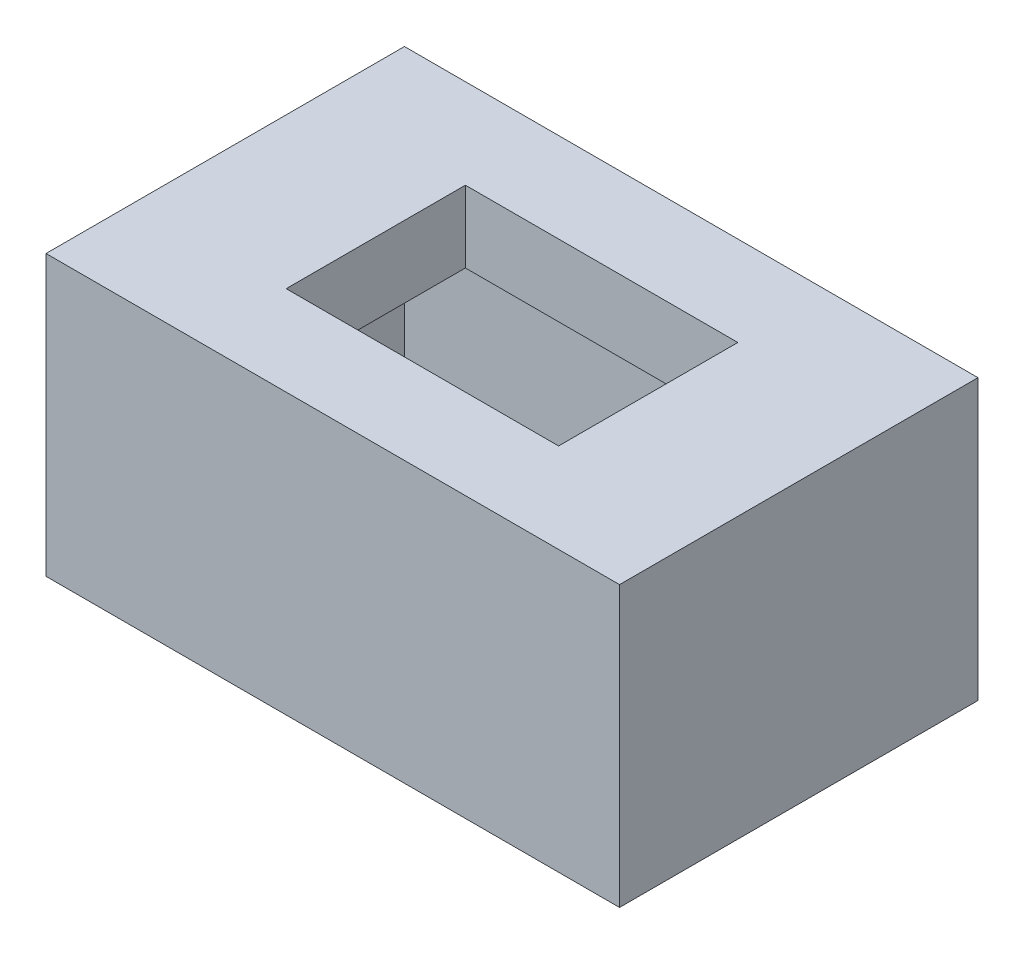
SolidWorks part; units mm, degrees
ref_plane "정면" through (0, 0, 0) normal (0, 0, 1) x (1, 0, 0)
ref_plane "윗면" through (0, 0, 0) normal (0, 1, 0) x (1, 0, 0)
ref_plane "우측면" through (0, 0, 0) normal (1, 0, 0) x (0, 0, -1)
sketch "스케치1" plane through (0, 0, 0) normal (0, 1, 0) x (1, 0, 0)
  line L1 (-40, 25) -> (40, 25)
  line L2 (-40, 25) -> (-40, -25)
  line L3 (-40, -25) -> (40, -25)
  line L4 (40, 25) -> (40, -25)
  line L5 (-40, 25) -> (40, -25) construction
  line L6 (-40, -25) -> (40, 25) construction
  point P0 (0, 0)
  dimension "D1" = 80
  dimension "D2" = 50
extrude "보스-돌출1" add sketch "스케치1" along normal blind 40
sketch "스케치2" plane through (0, 0, 0) normal (0, -1, 0) x (1, 0, 0)
  line L0 (35, -20) -> (35, 20)
  line L1 (35, 20) -> (-35, 20)
  line L2 (-35, 20) -> (-35, -20)
  line L3 (-35, -20) -> (35, -20)
  line L12 (-40, 25) -> (40, 25) construction
  line L13 (-40, -25) -> (-40, 25) construction
  line L14 (40, 25) -> (40, -25) construction
  line L15 (40, -25) -> (-40, -25) construction
  dimension "D1" = 5
  dimension "D2" = 5
  dimension "D3" = 5
  dimension "D4" = 5
extrude "컷-돌출1" cut sketch "스케치2" against normal blind 30
sketch "스케치4" plane through (0, 40, 0) normal (0, 1, 0) x (1, 0, 0)
  line L1 (-19, -12.5) -> (19, -12.5)
  line L2 (-19, -12.5) -> (-19, 12.5)
  line L3 (-19, 12.5) -> (19, 12.5)
  line L4 (19, -12.5) -> (19, 12.5)
  line L5 (-19, -12.5) -> (19, 12.5) construction
  line L6 (-19, 12.5) -> (19, -12.5) construction
  point P0 (0, 0)
  dimension "D1" = 38
  dimension "D2" = 25
extrude "컷-돌출2" cut sketch "스케치4" against normal blind 30
sketch "스케치7" plane through (0, 0, 0) normal (0, -1, 0) x (1, 0, 0)
  line L0 (37.5, -22.5) -> (37.5, 22.5)
  line L1 (37.5, 22.5) -> (-37.5, 22.5)
  line L2 (-37.5, 22.5) -> (-37.5, -22.5)
  line L3 (-37.5, -22.5) -> (37.5, -22.5)
  line L4 (40, -25) -> (40, 25)
  line L5 (40, 25) -> (-40, 25)
  line L6 (-40, 25) -> (-40, -25)
  line L7 (-40, -25) -> (40, -25)
  line L8 (40, -25) -> (40, 25)
  line L9 (40, 25) -> (-40, 25)
  line L10 (-40, 25) -> (-40, -25)
  line L11 (-40, -25) -> (40, -25)
  dimension "D1" = 0
  dimension "D2" = 2.5
extrude "컷-돌출3" cut sketch "스케치7" against normal blind 1
sketch "스케치8" plane through (0, 1, 0) normal (0, -1, 0) x (1, 0, 0)
  line L0 (-37.5, -22.5) -> (37.5, -22.5) construction
  line L1 (37.5, -22.5) -> (37.5, 22.5) construction
  line L2 (37.5, 22.5) -> (-37.5, 22.5) construction
  line L3 (-37.5, 22.5) -> (-37.5, -22.5) construction
  line L4 (-40, -25) -> (40, -25) construction
  line L5 (40, -25) -> (40, 25) construction
  line L6 (40, 25) -> (-40, 25) construction
  line L7 (-40, 25) -> (-40, -25) construction
  line L8 (-37.5, -22.5) -> (37.5, -22.5)
  line L9 (37.5, -22.5) -> (37.5, 22.5)
  line L10 (37.5, 22.5) -> (-37.5, 22.5)
  line L11 (-37.5, 22.5) -> (-37.5, -22.5)
  line L12 (-40, -25) -> (40, -25)
  line L13 (40, -25) -> (40, 25)
  line L14 (40, 25) -> (-40, 25)
  line L15 (-40, 25) -> (-40, -25)
  line L16 (-35, -20) -> (35, -20) construction
  line L17 (35, -20) -> (35, 20) construction
  line L18 (35, 20) -> (-35, 20) construction
  line L19 (-35, 20) -> (-35, -20) construction
  line L20 (-37.5, -22.5) -> (37.5, -22.5)
  line L21 (37.5, -22.5) -> (37.5, 22.5)
  line L22 (37.5, 22.5) -> (-37.5, 22.5)
  line L23 (-37.5, 22.5) -> (-37.5, -22.5)
  line L24 (-37.5, -22.5) -> (37.5, -22.5)
  line L25 (37.5, -22.5) -> (37.5, 22.5)
  line L26 (37.5, 22.5) -> (-37.5, 22.5)
  line L27 (-37.5, 22.5) -> (-37.5, -22.5)
  line L28 (-35, -20) -> (35, -20)
  line L29 (35, -20) -> (35, 20)
  line L30 (35, 20) -> (-35, 20)
  line L31 (-35, 20) -> (-35, -20)
  dimension "D1" = 0
